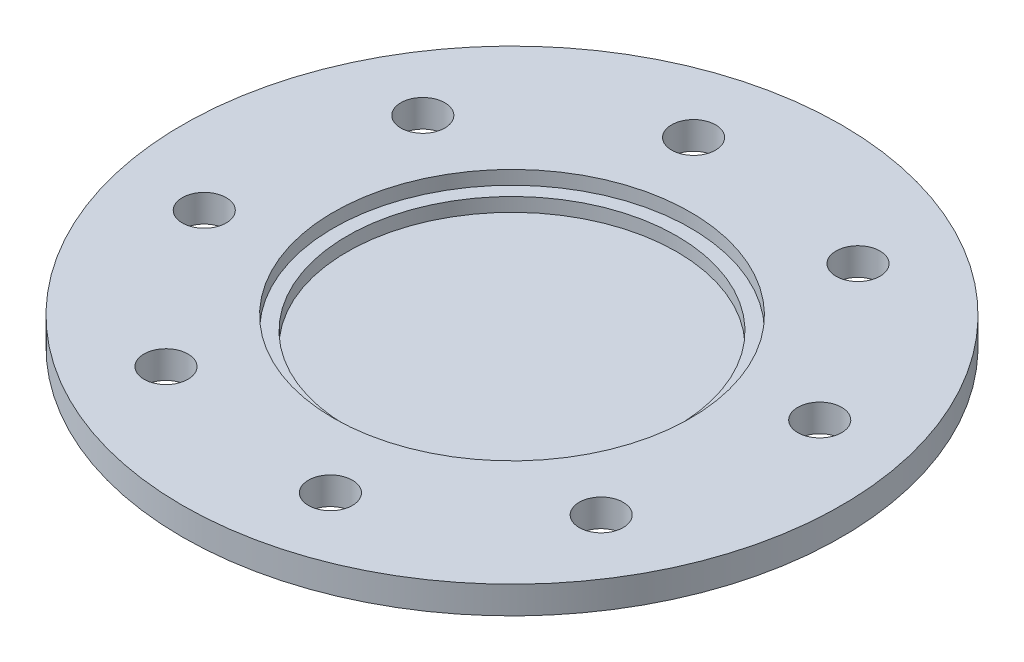
SolidWorks part; units mm, degrees
ref_plane "Front Plane" through (0, 0, 0) normal (0, 0, 1) x (1, 0, 0)
ref_plane "Top Plane" through (0, 0, 0) normal (0, 1, 0) x (1, 0, 0)
ref_plane "Right Plane" through (0, 0, 0) normal (1, 0, 0) x (0, 0, -1)
sketch "Sketch1" plane through (0, 0, 0) normal (0, 0, 1) x (1, 0, 0)
  line L0 (65, 41.2862) -> (120, 41.2862)
  line L1 (120, 41.2862) -> (120, 31.2862)
  line L2 (120, 31.2862) -> (75, 31.2862)
  line L3 (70, 26.2862) -> (70, 21.2862)
  line L4 (70, 21.2862) -> (60, 21.2862)
  line L5 (60, 36.2862) -> (60, 21.2862)
  line L7 (0, 97.7316) -> (0, 0) construction
  line L8 (65, 41.2862) -> (65, 36.2862)
  line L9 (65, 36.2862) -> (60, 36.2862)
  line L10 (75, 31.2862) -> (60, 31.2862) construction
  line L11 (60, 21.2862) -> (0, 21.2862)
  line L12 (0, 21.2862) -> (0, 31.2862)
  line L13 (0, 31.2862) -> (60, 31.2862)
  arc A0 (75, 31.2862) -> (70, 26.2862) centre (75, 26.2862) ccw
  point P10 (70, 31.2862)
  dimension "D5" = 5
  dimension "D1" = 65
  dimension "D2" = 10
  dimension "D3" = 10
  dimension "D4" = 10
  dimension "D6" = 60
  dimension "D7" = 15
  dimension "D8" = 120
revolve "Revolve1" add sketch "Sketch1" angle 360 about L7
sketch "Sketch2" plane through (0, 31.2862, 0) normal (0, -1, 0) x (1, 0, 0)
  circle A0 centre (0, 0) radius 92 construction
  circle A1 centre (79.234, 46.7544) radius 8
  point P3 (79.234, 46.7544)
  dimension "D1" = 16
  dimension "D2" = 92
extrude "Cut-Extrude1" cut sketch "Sketch2" against normal through all contours A1
pattern_circular "CirPattern1" count 8 over 360 about axis through (0, 0, 0) along (0, 1, 0) of "Cut-Extrude1"
